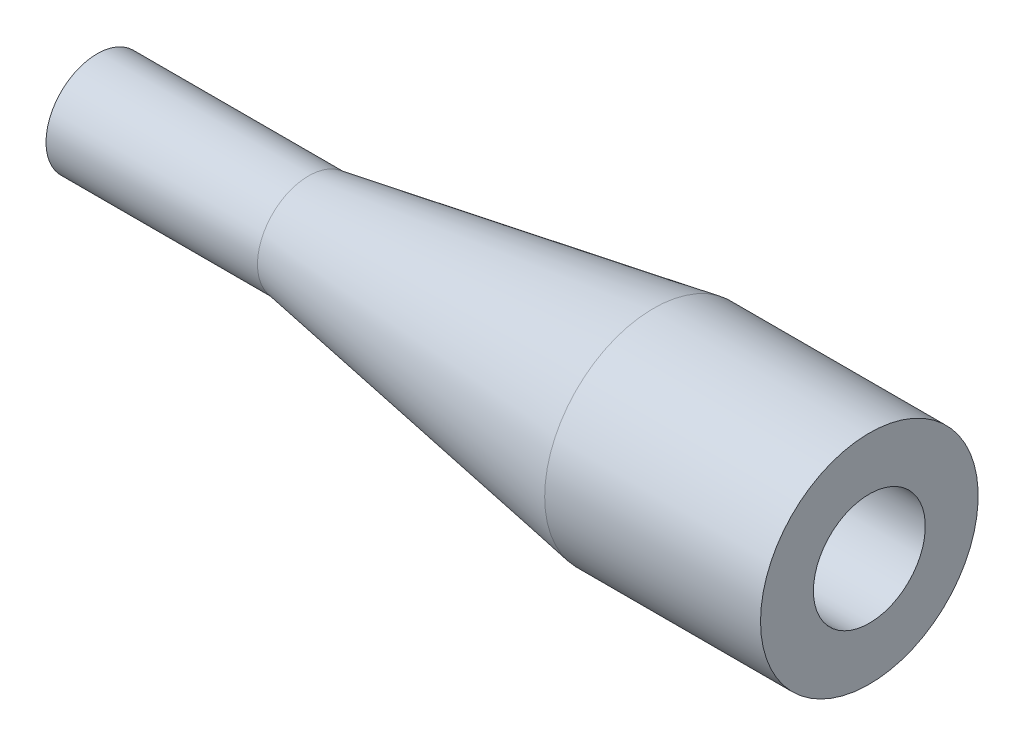
SolidWorks part; units mm, degrees
ref_plane "Front Plane" through (0, 0, 0) normal (0, 0, 1) x (1, 0, 0)
ref_plane "Top Plane" through (0, 0, 0) normal (0, 1, 0) x (1, 0, 0)
ref_plane "Right Plane" through (0, 0, 0) normal (1, 0, 0) x (0, 0, -1)
sketch "Sketch1" plane through (0, 0, 0) normal (0, 1, 0) x (1, 0, 0)
  line L0 (0, 0) -> (41.042, 0) construction
  line L1 (0, 0.9) -> (12, 0.9)
  line L2 (12, 0.9) -> (31.8207, 2.286)
  line L7 (12, 2.9) -> (0, 2.9)
  line L8 (0, 2.9) -> (0, 0.9)
  line L9 (31.8207, 2.286) -> (31.8207, 3.175)
  line L10 (31.8207, 3.175) -> (43.8207, 3.175)
  line L11 (43.8207, 3.175) -> (43.8207, 6.175)
  line L12 (12, 2.9) -> (31.5715, 6.175)
  line L13 (31.5715, 6.175) -> (43.8207, 6.175)
  dimension "D1" = 1.8
  dimension "D2" = 4
  dimension "D3" = 6.35
  dimension "D4" = 12
  dimension "D5" = 2
  dimension "D6" = 0.889
  dimension "D7" = 3
  dimension "D8" = 12
  dimension "D9" = 3
revolve "Revolve1" add sketch "Sketch1" angle 360 about L0
